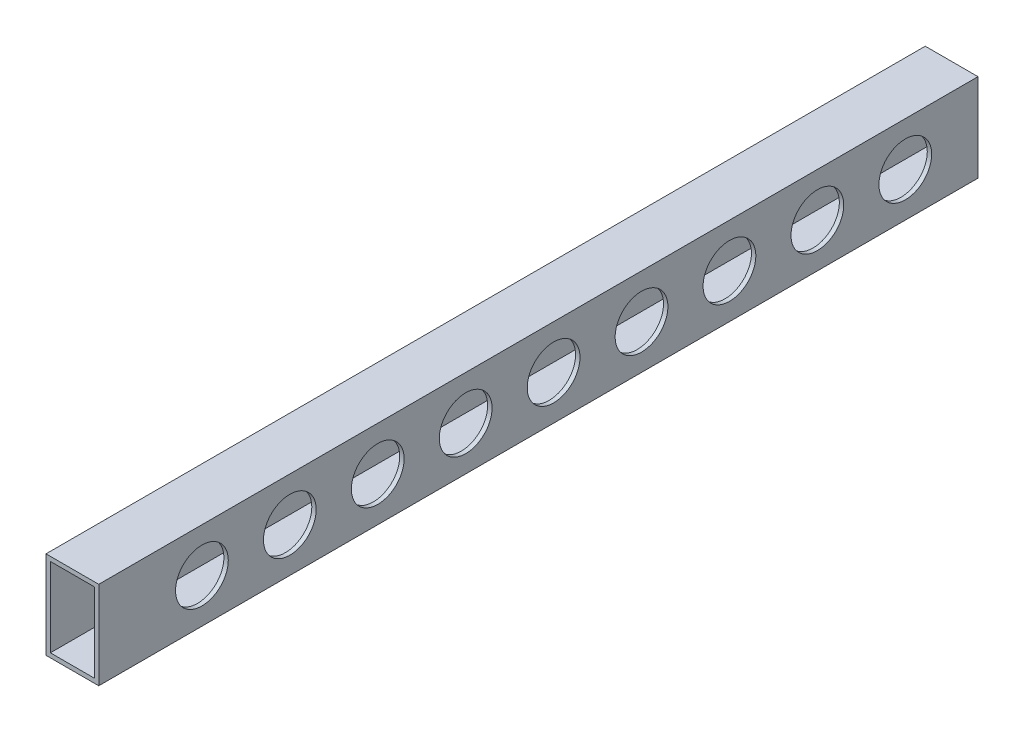
SolidWorks part; units mm, degrees
ref_plane "Front Plane" through (0, 0, 0) normal (0, 0, 1) x (1, 0, 0)
ref_plane "Top Plane" through (0, 0, 0) normal (0, 1, 0) x (1, 0, 0)
ref_plane "Right Plane" through (0, 0, 0) normal (1, 0, 0) x (0, 0, -1)
sketch "Sketch1" plane through (0, 0, 0) normal (0, 0, 1) x (1, 0, 0)
  line L1 (-19.05, -31.75) -> (19.05, -31.75)
  line L2 (-19.05, -31.75) -> (-19.05, 31.75)
  line L3 (-19.05, 31.75) -> (19.05, 31.75)
  line L4 (19.05, -31.75) -> (19.05, 31.75)
  line L5 (-19.05, -31.75) -> (19.05, 31.75) construction
  line L6 (-19.05, 31.75) -> (19.05, -31.75) construction
  line L7 (-15.875, -28.575) -> (15.875, -28.575)
  line L8 (-15.875, -28.575) -> (-15.875, 28.575)
  line L9 (-15.875, 28.575) -> (15.875, 28.575)
  line L10 (15.875, -28.575) -> (15.875, 28.575)
  line L11 (-15.875, -28.575) -> (15.875, 28.575) construction
  line L12 (-15.875, 28.575) -> (15.875, -28.575) construction
  point P0 (0, 0)
  point P1 (0, 0)
  point P7 (0, 0)
  dimension "D1" = 38.1
  dimension "D2" = 63.5
  dimension "D3" = 3.175
  dimension "D4" = 3.175
extrude "Boss-Extrude1" add sketch "Sketch1" along normal blind 635
sketch "Sketch2" plane through (19.05, 0, 0) normal (1, 0, 0) x (0, 0, -1)
  line L1 (-635, -31.75) -> (-635, 31.75) construction
  circle A0 centre (-560.5018, 0) radius 19.05
  circle A1 centre (-497.0018, 0) radius 19.05
  circle A2 centre (-433.5018, 0) radius 19.05
  circle A3 centre (-370.0018, 0) radius 19.05
  circle A4 centre (-306.5018, 0) radius 19.05
  circle A5 centre (-243.0018, 0) radius 19.05
  circle A6 centre (-179.5018, 0) radius 19.05
  circle A7 centre (-116.0018, 0) radius 19.05
  circle A8 centre (-52.5018, 0) radius 19.05
  dimension "D1" = 38.1
  dimension "D2" = 74.4982
  dimension "D3" = 9
extrude "Cut-Extrude1" cut sketch "Sketch2" against normal up to surface (38.1 mm away) up to face at (-19.05, 0, 317.5)
